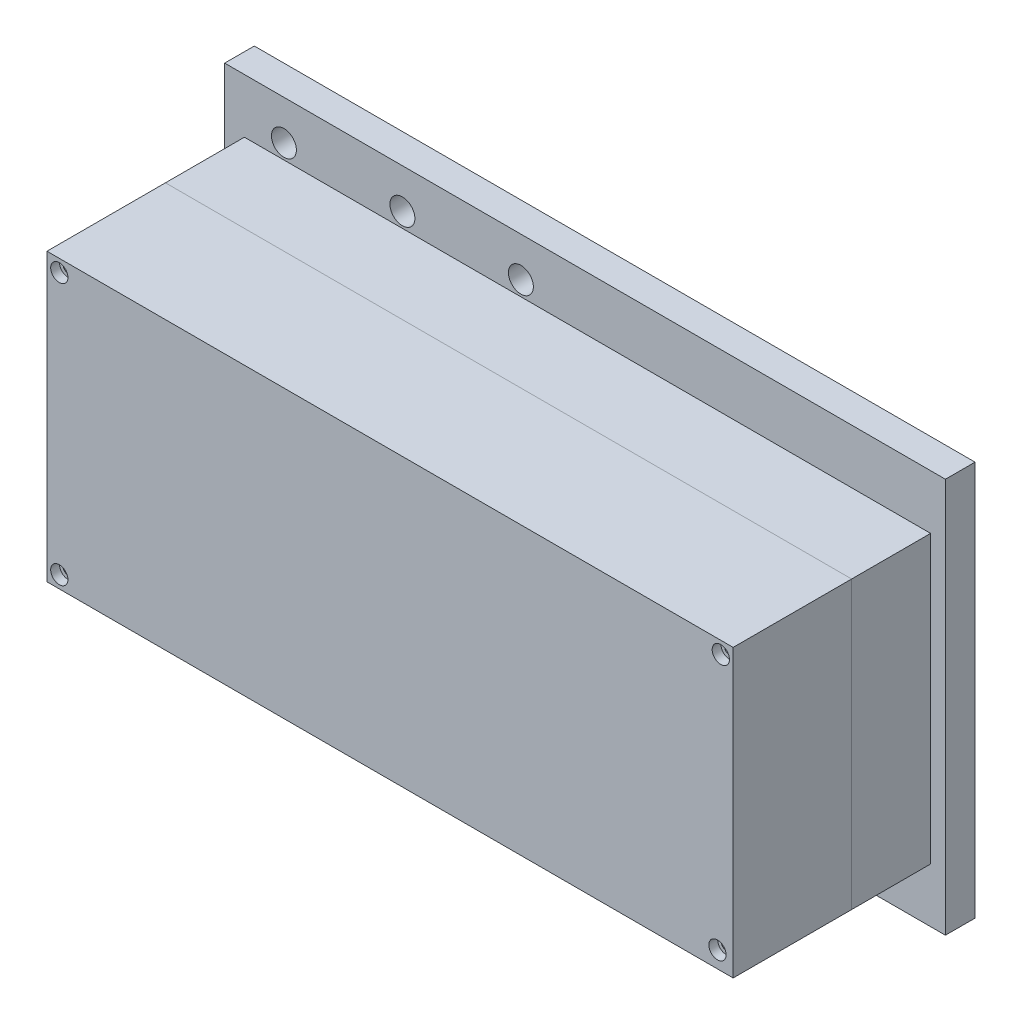
SolidWorks part; units mm, degrees
ref_plane "Front Plane" through (0, 0, 0) normal (0, 0, 1) x (1, 0, 0)
ref_plane "Top Plane" through (0, 0, 0) normal (0, 1, 0) x (1, 0, 0)
ref_plane "Right Plane" through (0, 0, 0) normal (1, 0, 0) x (0, 0, -1)
sketch "Sketch1" plane through (0, 0, 0) normal (0, 0, 1) x (1, 0, 0)
  line L1 (-115.8875, 63.5) -> (115.8875, 63.5)
  line L2 (-115.8875, 63.5) -> (-115.8875, -63.5)
  line L3 (-115.8875, -63.5) -> (115.8875, -63.5)
  line L4 (115.8875, 63.5) -> (115.8875, -63.5)
  line L5 (-115.8875, 63.5) -> (115.8875, -63.5) construction
  line L6 (-115.8875, -63.5) -> (115.8875, 63.5) construction
  point P0 (0, 0)
  dimension "D1" = 127
  dimension "D2" = 231.775
extrude "base" add sketch "Sketch1" along normal blind 9.525
hole_wizard "O (0.316) Diameter Hole1" positions "Sketch2" profile "Sketch3" hole size "O" standard "ANSI Inch" end condition up to next
sketch "Sketch2" plane through (0, 0, 9.525) normal (0, 0, 1) x (1, 0, 0)
  line L0 (-20.6375, -25.4) -> (-20.6375, -50.8)
  line L1 (-58.7375, -50.8) -> (-58.7375, -25.4)
  line L2 (-96.8375, -25.4) -> (-96.8375, -50.8)
  line L3 (-96.8375, -38.1) -> (-58.7375, -38.1)
  line L4 (-58.7375, -38.1) -> (-20.6375, -38.1)
  line L5 (-20.6375, 25.4) -> (-20.6375, 50.8)
  line L6 (-58.7375, 50.8) -> (-58.7375, 25.4)
  line L7 (-96.8375, 25.4) -> (-96.8375, 50.8)
  line L9 (-96.8375, 38.1) -> (-58.7375, 38.1)
  line L10 (-58.7375, 38.1) -> (-20.6375, 38.1)
  line L11 (-58.7375, -25.4) -> (-58.7375, 25.4) construction
  line L12 (-115.8875, 63.5) -> (-115.8875, -63.5) construction
  line L13 (-115.8875, 0) -> (-58.7375, 0) construction
  point P0 (-96.8375, 50.8)
  point P2 (-58.7375, 50.8)
  point P4 (-20.6375, 50.8)
  point P6 (-20.6375, 25.4)
  point P8 (-58.7375, 25.4)
  point P10 (-96.8375, 25.4)
  point P12 (-96.8375, -25.4)
  point P14 (-96.8375, -50.8)
  point P16 (-58.7375, -50.8)
  point P18 (-58.7375, -25.4)
  point P20 (-20.6375, -25.4)
  point P22 (-20.6375, -50.8)
  dimension "D1" = 57.15
  dimension "D2" = 76.2
  dimension "D3" = 38.1
  dimension "D4" = 25.4
sketch "Sketch3" plane through (-96.8375, 50.8, 9.525) normal (1, 0, 0) x (0, -1, 0)
  line L0 (0, 0) -> (0, 9.525)
  line L1 (0, 9.525) -> (4.0132, 9.525)
  line L2 (4.0132, 9.525) -> (4.0132, 0)
  line L5 (4.0132, 0) -> (0, 0)
  line L11 (0, -6.35) -> (0, 107.95) construction
  dimension "Thru Hole Dia." = 8.0264
  dimension "Thru Hole Depth" = 9.525
sketch "Sketch4" plane through (0, 0, 9.525) normal (0, 0, 1) x (1, 0, 0)
  line L0 (49.4348, 21.717) -> (-85.9472, -21.717) construction
  line L1 (-109.5375, 46.0375) -> (111.125, 46.0375)
  line L2 (-109.5375, 46.0375) -> (-109.5375, -46.0375)
  line L3 (-109.5375, -46.0375) -> (111.125, -46.0375)
  line L4 (111.125, 46.0375) -> (111.125, -46.0375)
  line L5 (111.125, 0) -> (103.1875, 0) construction
  line L6 (-101.6, 0) -> (-109.5375, 0) construction
  line L7 (-101.6, 38.1) -> (103.1875, 38.1)
  line L8 (-101.6, 38.1) -> (-101.6, -38.1)
  line L9 (-101.6, -38.1) -> (103.1875, -38.1)
  line L10 (103.1875, 38.1) -> (103.1875, -38.1)
  line L11 (-101.6, 38.1) -> (103.1875, -38.1) construction
  line L12 (-101.6, -38.1) -> (103.1875, 38.1) construction
  line L13 (49.4348, -21.717) -> (-85.9472, 21.717) construction
  line L14 (0.7937, 38.1) -> (0.7937, 46.0375) construction
  line L15 (-88.9, 25.4) -> (52.3875, 25.4) construction
  line L16 (-88.9, 25.4) -> (-88.9, -25.4) construction
  line L17 (-88.9, -25.4) -> (52.3875, -25.4) construction
  line L18 (52.3875, 25.4) -> (52.3875, -25.4) construction
  line L19 (-88.9, 25.4) -> (52.3875, -25.4) construction
  line L20 (-88.9, -25.4) -> (52.3875, 25.4) construction
  line L21 (0.7938, -46.0375) -> (0.7938, -38.1) construction
  line L22 (0.7938, -38.1) -> (0.7938, -25.4) construction
  line L23 (0.7937, 38.1) -> (0.7937, 25.4) construction
  line L24 (-115.8875, 63.5) -> (-115.8875, -63.5) construction
  point P5 (0.7938, 0)
  point P11 (-85.9472, 21.717)
  point P12 (-85.9472, -21.717)
  point P13 (49.4348, -21.717)
  point P14 (49.4348, 21.717)
  point P19 (-18.2563, 0)
  point P20 (-18.2563, 0)
  point P53 (-18.2563, 0)
  dimension "D1" = 43.434
  dimension "D2" = 135.382
  dimension "D3" = 7.9375
  dimension "D4" = 50.8
  dimension "D5" = 141.2875
  dimension "D6" = 12.7
  dimension "D7" = 12.7
  dimension "D8" = 50.8
  dimension "D9" = 6.35
extrude "Boss-Extrude2" add sketch "Sketch4" along normal blind 25.4
hole_wizard "#23 (0.154) Diameter Hole1" positions "Sketch6" profile "Sketch7" hole size "#23" standard "ANSI Inch" end condition up to next
sketch "Sketch6" plane through (0, 0, 9.525) normal (0, 0, 1) x (1, 0, 0)
  line L0 (74.8347, 22.733) -> (74.8347, -22.733) construction
  line L1 (49.4348, 21.717) -> (49.4348, -21.717) construction
  line L2 (49.4348, 0) -> (74.8347, 0) construction
  point P13 (74.8347, 22.733)
  point P15 (74.8347, -22.733)
  point P30 (-85.9472, 21.717)
  point P33 (49.4348, 21.717)
  point P36 (49.4348, -21.717)
  point P39 (-85.9472, -21.717)
  dimension "D1" = 45.466
  dimension "D2" = 25.4
sketch "Sketch7" plane through (74.8347, 22.733, 9.525) normal (1, 0, 0) x (0, -1, 0)
  line L0 (0, 0) -> (0, 9.525)
  line L1 (0, 9.525) -> (1.9558, 9.525)
  line L2 (1.9558, 9.525) -> (1.9558, 0.635)
  line L3 (1.9558, 0.635) -> (2.5908, 0)
  line L5 (2.5908, 0) -> (0, 0)
  line L6 (-1.9558, 0.635) -> (-2.5908, 0) construction
  line L11 (0, -6.35) -> (0, 107.95) construction
  dimension "Thru Hole Dia." = 3.9116
  dimension "Thru Hole Depth" = 9.525
  dimension "Near C'Sink Dia." = 5.1816
  dimension "Near C'Sink Angle" = 90
hole_wizard "#23 (0.154) Diameter Hole2" positions "Sketch8" profile "Sketch10" hole size "#23" standard "ANSI Inch"
sketch "Sketch8" plane through (0, 0, 34.925) normal (0, 0, 1) x (1, 0, 0)
  line L2 (103.1875, 38.1) -> (111.125, 46.0375) construction
  line L3 (103.1875, -38.1) -> (111.125, -46.0375) construction
  line L4 (-101.6, -38.1) -> (-109.5375, -46.0375) construction
  line L5 (-109.5375, 46.0375) -> (-101.6, 38.1) construction
  line L6 (103.1875, 38.1) -> (-101.6, 38.1) construction
  line L7 (-101.6, 38.1) -> (-101.6, -38.1) construction
  point P0 (-105.5688, 42.0687)
  point P2 (-105.5687, -42.0688)
  point P4 (106.0879, -40.7274)
  point P6 (107.1562, 42.0688)
sketch "Sketch10" plane through (-105.5688, 42.0687, 34.925) normal (1, 0, 0) x (0, -1, 0)
  line L0 (0, 0) -> (0, 13.8752)
  line L1 (0, 13.8752) -> (1.9558, 12.7)
  line L2 (1.9558, 12.7) -> (1.9558, 0.635)
  line L3 (1.9558, 0.635) -> (2.5908, 0)
  line L5 (2.5908, 0) -> (0, 0)
  line L6 (-1.9558, 0.635) -> (-2.5908, 0) construction
  line L10 (0, 13.8752) -> (-1.9558, 12.7) construction
  line L11 (0, -6.35) -> (0, 107.95) construction
  dimension "Hole Dia." = 3.9116
  dimension "Hole Depth" = 12.7
  dimension "Near C'Sink Dia." = 5.1816
  dimension "Near C'Sink Angle" = 90
  dimension "Drill Angle" = 118
sketch "Sketch11" plane through (0, -46.0375, 0) normal (0, -1, 0) x (1, 0, 0)
  line L0 (-95.25, 34.925) -> (-95.25, 22.225)
  line L1 (-109.5375, 34.925) -> (111.125, 34.925) construction
  line L2 (-95.25, 22.225) -> (96.8375, 22.225)
  line L3 (96.8375, 22.225) -> (96.8375, 34.925)
  line L4 (96.8375, 34.925) -> (-95.25, 34.925)
  line L5 (-101.6, 34.925) -> (-101.6, 9.525) construction
  dimension "D1" = 12.7
  dimension "D2" = 6.35
  dimension "D3" = 6.35
extrude "Cut-Extrude1" cut sketch "Sketch11" against normal up to next
sketch "Sketch12" plane through (-109.5375, 0, 0) normal (-1, 0, 0) x (0, 0, 1)
  line L0 (34.925, 46.0375) -> (34.925, -46.0375) construction
  line L1 (34.925, 31.75) -> (22.225, 31.75)
  line L2 (34.925, 31.75) -> (34.925, -31.75)
  line L3 (34.925, -31.75) -> (22.225, -31.75)
  line L4 (22.225, 31.75) -> (22.225, -31.75)
  line L5 (34.925, 31.75) -> (22.225, -31.75) construction
  line L6 (34.925, -31.75) -> (22.225, 31.75) construction
  point P0 (28.575, 0)
  dimension "D1" = 6.35
  dimension "D2" = 6.35
  dimension "D3" = 12.7
extrude "Cut-Extrude2" cut sketch "Sketch12" against normal up to next
ref_plane "Plane1" through (0, 0, 66.675) normal (0, 0, 1) x (1, 0, 0)
sketch "Sketch13" plane through (0, 0, 66.675) normal (0, 0, 1) x (1, 0, 0)
  line L0 (-101.6, 31.75) -> (-109.5375, 31.75)
  line L1 (-109.5375, 31.75) -> (-109.5375, 46.0375)
  line L2 (-109.5375, 46.0375) -> (111.125, 46.0375)
  line L3 (111.125, 46.0375) -> (111.125, -46.0375)
  line L4 (111.125, -46.0375) -> (96.8375, -46.0375)
  line L5 (96.8375, -46.0375) -> (96.8375, -38.1)
  line L6 (96.8375, -38.1) -> (103.1875, -38.1)
  line L7 (103.1875, -38.1) -> (103.1875, 38.1)
  line L8 (103.1875, 38.1) -> (-101.6, 38.1)
  line L9 (-101.6, 38.1) -> (-101.6, 31.75)
  line L10 (-101.6, -31.75) -> (-109.5375, -31.75)
  line L11 (-109.5375, -31.75) -> (-109.5375, -46.0375)
  line L12 (-109.5375, -46.0375) -> (-95.25, -46.0375)
  line L13 (-95.25, -46.0375) -> (-95.25, -38.1)
  line L14 (-95.25, -38.1) -> (-101.6, -38.1)
  line L15 (-101.6, -38.1) -> (-101.6, -31.75)
  line L16 (-109.5375, -46.0375) -> (-95.25, -46.0375) construction
  line L17 (-95.25, -38.1) -> (-95.25, -46.0375) construction
  line L18 (-101.6, -38.1) -> (-95.25, -38.1) construction
  line L19 (-101.6, -31.75) -> (-101.6, -38.1) construction
  line L20 (-101.6, -31.75) -> (-109.5375, -31.75) construction
  line L21 (-109.5375, -31.75) -> (-109.5375, -46.0375) construction
  line L22 (-101.6, 31.75) -> (-109.5375, 31.75) construction
  line L23 (-101.6, 38.1) -> (-101.6, 31.75) construction
  line L24 (-109.5375, 46.0375) -> (-109.5375, 31.75) construction
  line L25 (111.125, 46.0375) -> (-109.5375, 46.0375) construction
  line L26 (103.1875, 38.1) -> (-101.6, 38.1) construction
  line L27 (103.1875, -38.1) -> (103.1875, 38.1) construction
  line L29 (96.8375, -38.1) -> (103.1875, -38.1) construction
  line L30 (96.8375, -46.0375) -> (111.125, -46.0375) construction
  line L31 (96.8375, -38.1) -> (96.8375, -46.0375) construction
  line L32 (111.125, -46.0375) -> (111.125, 46.0375) construction
  point P48 (0, 0)
  point P50 (95.1079, 27.8062)
extrude "Boss-Extrude3" add sketch "Sketch13" against normal up to surface (31.75 mm away) separate body up to face at (20.0025, 6.35, 34.925)
sketch "Sketch14" plane through (0, 0, 66.675) normal (0, 0, 1) x (1, 0, 0)
  line L0 (-109.5375, 46.0375) -> (-109.5375, -46.0375)
  line L1 (-109.5375, -46.0375) -> (111.125, -46.0375)
  line L2 (111.125, -46.0375) -> (111.125, 46.0375)
  line L3 (111.125, 46.0375) -> (-109.5375, 46.0375)
extrude "Boss-Extrude4" add sketch "Sketch14" along normal blind 6.35
hole_wizard "CBORE for #4 Socket Head Cap Screw1" positions "Sketch15" profile "Sketch16" counterbore size "#4" standard "ANSI Inch" end condition up to next
sketch "Sketch15" plane through (0, 0, 73.025) normal (0, 0, 1) x (1, 0, 0)
  circle A0 centre (-105.5687, -42.0688) radius 2.5908 construction
  circle A1 centre (106.0879, -40.7274) radius 2.5908 construction
  circle A2 centre (107.1562, 42.0688) radius 2.5908 construction
  circle A3 centre (-105.5688, 42.0687) radius 2.5908 construction
  point P0 (-105.5687, -42.0688)
  point P2 (-105.5688, 42.0687)
  point P4 (107.1562, 42.0688)
  point P6 (106.0879, -40.7274)
  point P10 (0, 0)
  point P11 (0, 0)
  point P14 (0, 0)
  point P15 (0, 0)
  point P18 (0, 0)
  point P21 (0, 0)
sketch "Sketch16" plane through (-105.5687, -42.0688, 73.025) normal (1, 0, 0) x (0, -1, 0)
  line L0 (0, 0) -> (0, 73.025)
  line L1 (0, 73.025) -> (1.6319, 73.025)
  line L3 (1.6319, 73.025) -> (1.632, 2.8448)
  line L4 (1.632, 2.8448) -> (2.7788, 2.8448)
  line L5 (2.7788, 2.8448) -> (2.7788, 0)
  line L7 (2.7788, 0) -> (0, 0)
  line L11 (0, -6.35) -> (0, 107.95) construction
  dimension "Thru Hole Dia." = 3.2639
  dimension "Thru Hole Depth" = 73.025
  dimension "C'Bore Dia." = 5.5575
  dimension "C'Bore Depth" = 2.8448
fillet "Fillet1" radius 2.54 18 edges at (96.8375, -46.0375, 50.8) (-109.5375, 31.75, 50.8) (-109.5375, -31.75, 50.8) (-95.25, -46.0375, 50.8) (96.8375, -42.0688, 66.675) (100.0125, -38.1, 66.675) (103.1875, 0, 66.675) (0.7937, 38.1, 66.675) (-101.6, 34.925, 66.675) (-105.5688, 31.75, 66.675) (-109.5375, 0, 66.675) (-105.5687, -31.75, 66.675) (-101.6, -34.925, 66.675) (-98.425, -38.1, 66.675) (-95.25, -42.0688, 66.675) (0.7938, -46.0375, 66.675) (103.1875, 38.1, 50.8) (-101.6, 38.1, 50.8)
